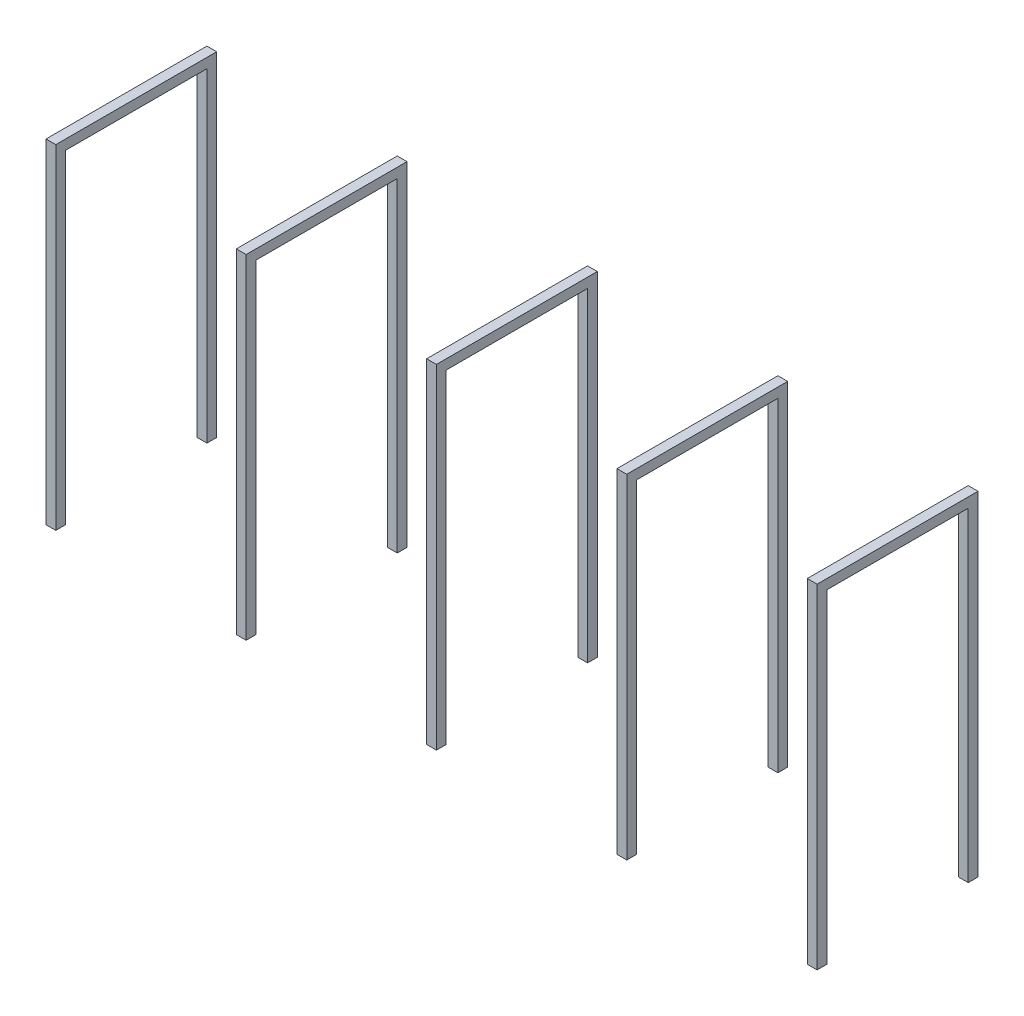
SolidWorks part; units mm, degrees
ref_plane "Alzado" through (0, 0, 0) normal (0, 0, 1) x (1, 0, 0)
ref_plane "Planta" through (0, 0, 0) normal (0, 1, 0) x (1, 0, 0)
ref_plane "Vista lateral" through (0, 0, 0) normal (1, 0, 0) x (0, 0, -1)
sketch "Croquis1" plane through (0, 0, 0) normal (0, 1, 0) x (1, 0, 0)
  line L0 (76.2, 0) -> (1481.2, 0) construction
  line L1 (0, 0) -> (76.2, 0)
  line L2 (0, 0) -> (0, -76.2)
  line L3 (0, -76.2) -> (76.2, -76.2)
  line L4 (76.2, 0) -> (76.2, -76.2)
  line L5 (1557.4, 0) -> (2962.4, 0) construction
  line L6 (1481.2, 0) -> (1557.4, 0)
  line L7 (1481.2, 0) -> (1481.2, -76.2)
  line L8 (1481.2, -76.2) -> (1557.4, -76.2)
  line L9 (1557.4, 0) -> (1557.4, -76.2)
  line L10 (3038.6, 0) -> (4443.6, 0) construction
  line L11 (2962.4, 0) -> (3038.6, 0)
  line L12 (2962.4, 0) -> (2962.4, -76.2)
  line L13 (2962.4, -76.2) -> (3038.6, -76.2)
  line L14 (3038.6, 0) -> (3038.6, -76.2)
  line L15 (4519.8, 0) -> (5924.8, 0) construction
  line L16 (4443.6, 0) -> (4519.8, 0)
  line L17 (4443.6, 0) -> (4443.6, -76.2)
  line L18 (4443.6, -76.2) -> (4519.8, -76.2)
  line L19 (4519.8, 0) -> (4519.8, -76.2)
  line L20 (0, -76.2) -> (0, -626.2) construction
  line L21 (5924.8, 0) -> (6001, 0)
  line L22 (5924.8, 0) -> (5924.8, -76.2)
  line L23 (5924.8, -76.2) -> (6001, -76.2)
  line L24 (6001, 0) -> (6001, -76.2)
  line L25 (0, -626.2) -> (6001, -626.2) construction
  line L26 (4519.8, -1252.4) -> (5924.8, -1252.4) construction
  line L27 (3038.6, -1252.4) -> (4443.6, -1252.4) construction
  line L28 (1557.4, -1252.4) -> (2962.4, -1252.4) construction
  line L29 (76.2, -1252.4) -> (1481.2, -1252.4) construction
  line L30 (6001, -626.2) -> (6001, -76.2) construction
  line L31 (6001, -1252.4) -> (6001, -1176.2)
  line L32 (5924.8, -1176.2) -> (6001, -1176.2)
  line L33 (5924.8, -1252.4) -> (5924.8, -1176.2)
  line L34 (5924.8, -1252.4) -> (6001, -1252.4)
  line L35 (4519.8, -1252.4) -> (4519.8, -1176.2)
  line L36 (4443.6, -1176.2) -> (4519.8, -1176.2)
  line L37 (4443.6, -1252.4) -> (4443.6, -1176.2)
  line L38 (4443.6, -1252.4) -> (4519.8, -1252.4)
  line L39 (3038.6, -1252.4) -> (3038.6, -1176.2)
  line L40 (2962.4, -1176.2) -> (3038.6, -1176.2)
  line L41 (2962.4, -1252.4) -> (2962.4, -1176.2)
  line L42 (2962.4, -1252.4) -> (3038.6, -1252.4)
  line L43 (1557.4, -1252.4) -> (1557.4, -1176.2)
  line L44 (1481.2, -1176.2) -> (1557.4, -1176.2)
  line L45 (1481.2, -1252.4) -> (1481.2, -1176.2)
  line L46 (1481.2, -1252.4) -> (1557.4, -1252.4)
  line L47 (76.2, -1252.4) -> (76.2, -1176.2)
  line L48 (0, -1176.2) -> (76.2, -1176.2)
  line L49 (0, -1252.4) -> (0, -1176.2)
  line L50 (0, -1252.4) -> (76.2, -1252.4)
  dimension "D1" = 76.2
  dimension "D2" = 76.2
  dimension "D3" = 1405
  dimension "D4" = 76.2
  dimension "D5" = 76.2
  dimension "D6" = 1405
  dimension "D7" = 76.2
  dimension "D8" = 76.2
  dimension "D9" = 1405
  dimension "D10" = 76.2
  dimension "D11" = 76.2
  dimension "D12" = 1405
  dimension "D13" = 76.2
  dimension "D14" = 76.2
  dimension "D15" = 550
extrude "Saliente-Extruir1" add sketch "Croquis1" along normal blind 2600
sketch "Croquis2" plane through (0, 0, 76.2) normal (0, 0, 1) x (1, 0, 0)
  line L0 (76.2, 2600) -> (76.2, 0) construction
  line L1 (0, 2600) -> (76.2, 2600)
  line L2 (0, 2600) -> (0, 2523.8)
  line L3 (0, 2523.8) -> (76.2, 2523.8)
  line L4 (76.2, 2600) -> (76.2, 2523.8)
  line L5 (1557.4, 2600) -> (1557.4, 0) construction
  line L6 (1481.2, 2600) -> (1557.4, 2600)
  line L7 (1481.2, 2600) -> (1481.2, 2523.8)
  line L8 (1481.2, 2523.8) -> (1557.4, 2523.8)
  line L9 (1557.4, 2600) -> (1557.4, 2523.8)
  line L10 (3038.6, 2600) -> (3038.6, 0) construction
  line L11 (2962.4, 2600) -> (3038.6, 2600)
  line L12 (2962.4, 2600) -> (2962.4, 2523.8)
  line L13 (2962.4, 2523.8) -> (3038.6, 2523.8)
  line L14 (3038.6, 2600) -> (3038.6, 2523.8)
  line L15 (4519.8, 2600) -> (4519.8, 0) construction
  line L16 (4443.6, 2600) -> (4519.8, 2600)
  line L17 (4443.6, 2600) -> (4443.6, 2523.8)
  line L18 (4443.6, 2523.8) -> (4519.8, 2523.8)
  line L19 (4519.8, 2600) -> (4519.8, 2523.8)
  line L20 (6001, 2600) -> (6001, 0) construction
  line L21 (5924.8, 2600) -> (6001, 2600)
  line L22 (5924.8, 2600) -> (5924.8, 2523.8)
  line L23 (5924.8, 2523.8) -> (6001, 2523.8)
  line L24 (6001, 2600) -> (6001, 2523.8)
  dimension "D1" = 76.2
  dimension "D2" = 76.2
  dimension "D3" = 76.2
extrude "Saliente-Extruir2" add sketch "Croquis2" along normal up to surface (1100 mm away) up to face at (5962.9, 1300, 1176.2)
